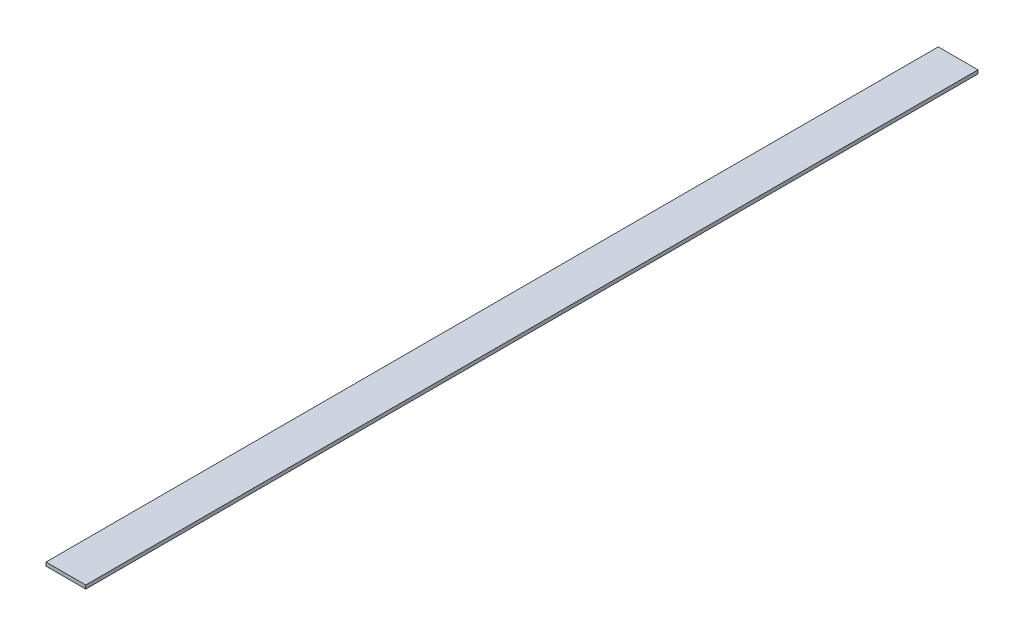
SolidWorks part; units mm, degrees
ref_plane "Front Plane" through (0, 0, 0) normal (0, 0, 1) x (1, 0, 0)
ref_plane "Top Plane" through (0, 0, 0) normal (0, 1, 0) x (1, 0, 0)
ref_plane "Right Plane" through (0, 0, 0) normal (1, 0, 0) x (0, 0, -1)
sketch "Sketch1" plane through (0, 0, 0) normal (0, 0, 1) x (1, 0, 0)
  line L1 (0, 0) -> (110, 0)
  line L2 (0, 0) -> (0, -10)
  line L3 (0, -10) -> (110, -10)
  line L4 (110, 0) -> (110, -10)
  dimension "D1" = 10
  dimension "D2" = 110
extrude "Boss-Extrude1" add sketch "Sketch1" along normal blind 2470
